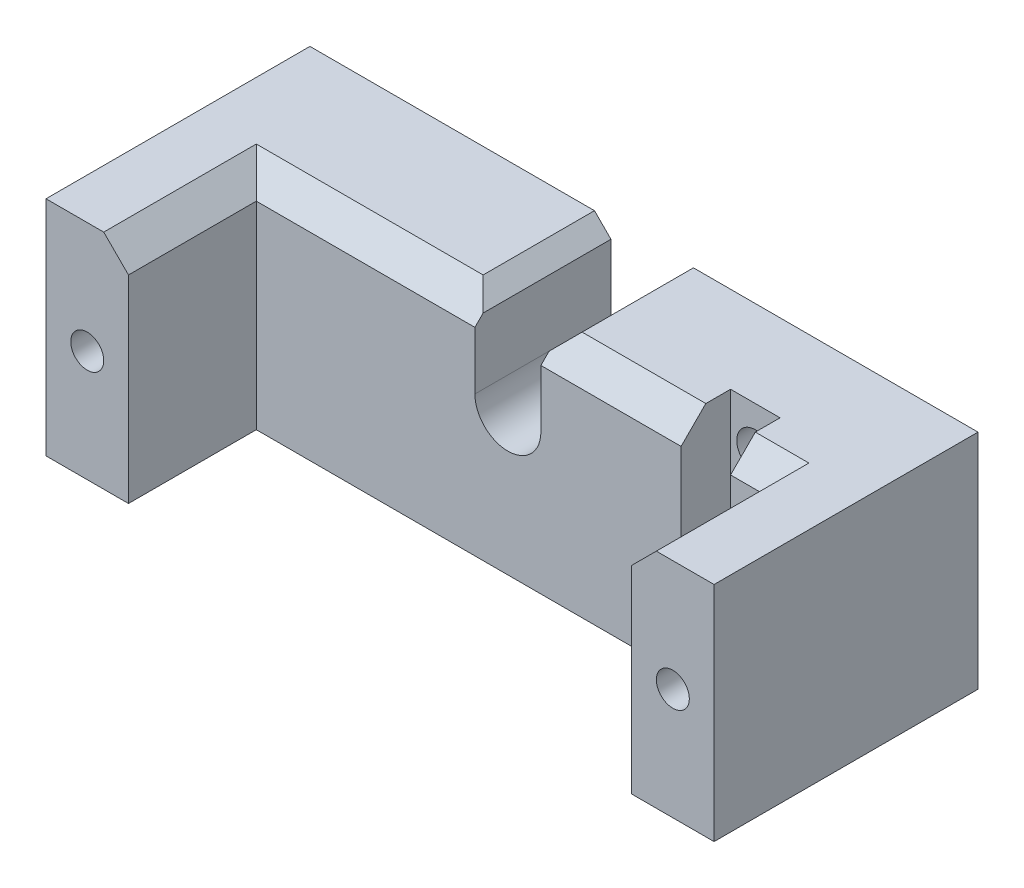
SolidWorks part; units mm, degrees
ref_plane "Plan de face" through (0, 0, 0) normal (0, 0, 1) x (1, 0, 0)
ref_plane "Plan de dessus" through (0, 0, 0) normal (0, 1, 0) x (1, 0, 0)
ref_plane "Plan de droite" through (0, 0, 0) normal (1, 0, 0) x (0, 0, -1)
sketch "Esquisse5" plane through (0, 0, 0) normal (0, 0, 1) x (1, 0, 0)
  line L1 (-30.5, 13.5) -> (30.5, 13.5)
  line L2 (-30.5, 13.5) -> (-30.5, -13.5)
  line L3 (-30.5, -13.5) -> (30.5, -13.5)
  line L4 (30.5, 13.5) -> (30.5, -13.5)
  line L5 (-30.5, 13.5) -> (30.5, -13.5) construction
  line L6 (-30.5, -13.5) -> (30.5, 13.5) construction
  point P0 (0, 0)
  dimension "D1" = 27
  dimension "D2" = 61
extrude "Boss.-Extru.2" add sketch "Esquisse5" along normal blind 16.5
sketch "Esquisse6" plane through (0, 0, 16.5) normal (0, 0, 1) x (1, 0, 0)
  line L1 (-4, 38.5244) -> (4, 38.5244)
  line L2 (-4, 38.5244) -> (-4, 3.5)
  line L4 (4, 38.5244) -> (4, 3.5)
  line L5 (-4, 38.5244) -> (4, 3.5) construction
  line L6 (-4, 3.5) -> (4, 38.5244) construction
  line L8 (0, 3.5) -> (0, 0.0643) construction
  line L10 (0, -0.5) -> (8.0499, -0.5) construction
  line L12 (-30.5, 13.5) -> (-30.5, -13.5) construction
  line L13 (-30.5, -13.5) -> (30.5, -13.5) construction
  arc A0 (-4, 3.5) -> (4, 3.5) centre (0, 3.5) ccw
  dimension "D5" = 4
  dimension "D1" = 8
  dimension "D2" = 30.5
  dimension "D3" = 13
  dimension "D4" = 8
extrude "Enlèv. mat.-Extru.2" cut sketch "Esquisse6" against normal blind 16.5
sketch "Esquisse7" plane through (0, 0, 0) normal (0, 0, -1) x (-1, 0, 0)
  line L1 (-30.5, -13.5) -> (-40.5, -13.5)
  line L2 (-30.5, -13.5) -> (-30.5, 13.5)
  line L3 (-30.5, 13.5) -> (-40.5, 13.5)
  line L4 (-40.5, -13.5) -> (-40.5, 13.5)
  line L5 (30.5, 13.5) -> (40.5, 13.5)
  line L6 (30.5, 13.5) -> (30.5, -13.5)
  line L7 (30.5, -13.5) -> (40.5, -13.5)
  line L8 (40.5, 13.5) -> (40.5, -13.5)
  dimension "D1" = 10
extrude "Boss.-Extru.3" add sketch "Esquisse7" against normal blind 32
sketch "Esquisse8" plane through (0, 0, 32) normal (0, 0, 1) x (1, 0, 0)
  circle A0 centre (-35.5, 0) radius 2
  circle A1 centre (35.5, 0) radius 2
  dimension "D1" = 4
  dimension "D2" = 4
extrude "Enlèv. mat.-Extru.3" cut sketch "Esquisse8" against normal blind 40
sketch "Esquisse9" plane through (0, 0, 0) normal (0, 0, -1) x (-1, 0, 0)
  circle A0 centre (-35.5, 0) radius 3.75
  circle A1 centre (35.5, 0) radius 3.75
  dimension "D1" = 7.5
  dimension "D2" = 7.5
extrude "Enlèv. mat.-Extru.4" cut sketch "Esquisse9" against normal blind 4
chamfer "Chanfrein1" distance 2 angle 45 2 edges at (-4, 13.5, 8.25) (4, 13.5, 8.25)
chamfer "Chanfrein2" distance 3 angle 45 2 edges at (-30.5, 13.5, 24.25) (30.5, 13.5, 24.25)
sketch "Esquisse10" plane through (0, 13.5, 0) normal (0, 1, 0) x (1, 0, 0)
  line L0 (33.5, -16.5) -> (6, -16.5) construction
  line L1 (27, -16.5) -> (21, -16.5)
  line L2 (27, -16.5) -> (27, -10.5)
  line L3 (27, -10.5) -> (21, -10.5)
  line L4 (21, -16.5) -> (21, -10.5)
  line L5 (40.5, -32) -> (40.5, 0) construction
  dimension "D1" = 6
  dimension "D2" = 6
  dimension "D3" = 13.5
extrude "Enlèv. mat.-Extru.5" cut sketch "Esquisse10" against normal blind 36
sketch "Esquisse11" plane through (0, 0, 10.5) normal (0, 0, 1) x (1, 0, 0)
  line L0 (27, -13.5) -> (21, -13.5) construction
  line L1 (27, 13.5) -> (21, 13.5) construction
  line L3 (40.5, 13.5) -> (40.5, -13.5) construction
  circle A0 centre (24, 8.5) radius 2.25
  circle A1 centre (24, -8.5) radius 2.25
  dimension "D1" = 4.5
  dimension "D2" = 5
  dimension "D3" = 5
  dimension "D4" = 16.5
  dimension "D5" = 16.5
extrude "Enlèv. mat.-Extru.6" cut sketch "Esquisse11" against normal blind 8
sketch "Esquisse12" plane through (0, 0, 2.5) normal (0, 0, 1) x (1, 0, 0)
  circle A0 centre (24, 8.5) radius 1.5
  circle A1 centre (24, -8.5) radius 1.5
  dimension "D1" = 3
extrude "Enlèv. mat.-Extru.7" cut sketch "Esquisse12" against normal blind 8
chamfer "Chanfrein3" distance 3 angle 45 3 edges at (30.25, 13.5, 16.5) (13.5, 13.5, 16.5) (-19.75, 13.5, 16.5)
